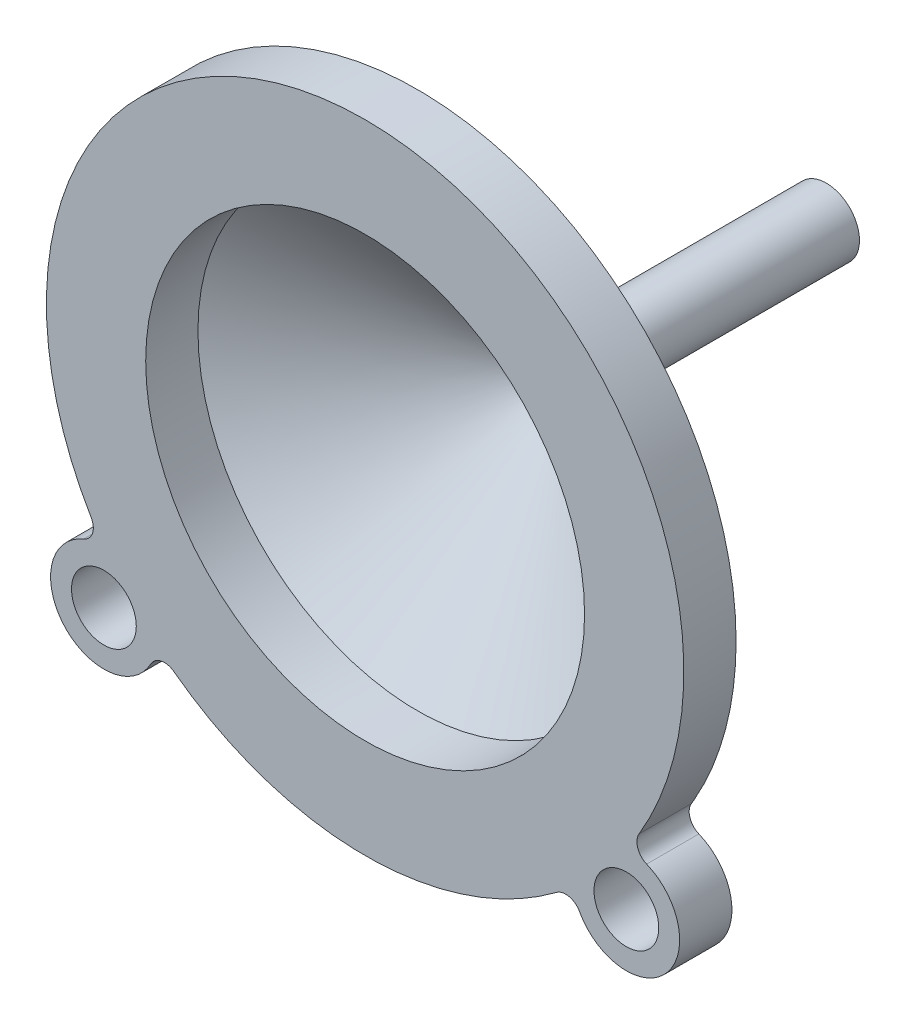
SolidWorks part; units mm, degrees
ref_plane "Plano frontal" through (0, 0, 0) normal (0, 0, 1) x (1, 0, 0)
ref_plane "Plano superior" through (0, 0, 0) normal (0, 1, 0) x (1, 0, 0)
ref_plane "Plano direito" through (0, 0, 0) normal (1, 0, 0) x (0, 0, -1)
sketch "Esboço1" plane through (0, 0, 0) normal (0, 0, 1) x (1, 0, 0)
  line L0 (0, 0) -> (-25, -22.4491) construction
  line L1 (0, 0) -> (25, -22.4491) construction
  line L2 (25, -22.4491) -> (-25, -22.4491) construction
  line L3 (0, 0) -> (0, -22.4491) construction
  arc A0 (26.2211, -15.579) -> (-26.2211, -15.579) centre (0, 0) ccw
  circle A1 centre (0, 0) radius 21
  circle A2 centre (25, -22.4491) radius 3.1
  circle A3 centre (-25, -22.4491) radius 3.1
  arc A5 (26.2211, -15.579) -> (26.94, -17.7325) centre (27.5106, -16.3452) ccw
  arc A6 (-26.94, -17.7325) -> (-20.5186, -24.8836) centre (-25, -22.4491) ccw
  arc A7 (-26.94, -17.7325) -> (-26.2211, -15.579) centre (-27.5106, -16.3452) ccw
  arc A8 (-18.3005, -24.3996) -> (-20.5186, -24.8836) centre (-19.2005, -25.5996) ccw
  arc A9 (20.5186, -24.8836) -> (18.3005, -24.3996) centre (19.2005, -25.5996) ccw
  arc A10 (20.5186, -24.8836) -> (26.94, -17.7325) centre (25, -22.4491) ccw
  arc A11 (-18.3005, -24.3996) -> (18.3005, -24.3996) centre (0, 0) ccw
  point P1 (26.2211, -15.579)
  point P9 (20.5186, -24.2363)
  point P14 (25, -22.4491)
  point P18 (0, 0)
  point P24 (0, 0)
  point P25 (20.4226, -24.698)
  dimension "D1" = 61
  dimension "D2" = 42
  dimension "D4" = 6.2
  dimension "D5" = 3
  dimension "D6" = 2
  dimension "D7" = 2
  dimension "D3" = 50
extrude "Ressalto-extrusão1" add sketch "Esboço1" along normal blind 5
sketch "Esboço2" plane through (0, 0, 0) normal (0, 1, 0) x (1, 0, 0)
  line L0 (30.5, 0) -> (3.175, 19.1332)
  line L1 (3.175, 19.1332) -> (3.175, 39.1332)
  line L2 (3.175, 39.1332) -> (1.675, 39.1332)
  line L3 (1.675, 39.1332) -> (1.675, 13.5315)
  line L4 (1.675, 13.5315) -> (21, 0)
  line L5 (30.5, 0) -> (-30.5, 0) construction
  line L6 (21, 0) -> (-21, 0) construction
  line L7 (21, -5) -> (21, 0) construction
  line L8 (21, 0) -> (30.5, 0)
  line L9 (0, 0) -> (0, 56.2866) construction
  dimension "D1" = 3.175
  dimension "D2" = 35
  dimension "D3" = 1.5
  dimension "D4" = 20
revolve "Revolução1" add sketch "Esboço2" angle 360 about L9
sketch "Esboço3" plane through (0, 0, 0) normal (0, 0, -1) x (-1, 0, 0)
  circle A0 centre (-25, -22.4491) radius 7.5
  circle A1 centre (25, -22.4491) radius 7.5
  circle A2 centre (25, -22.4491) radius 3.1 construction
  dimension "D1" = 15
extrude "Corte-extrusão1" cut sketch "Esboço3" along normal blind 19
